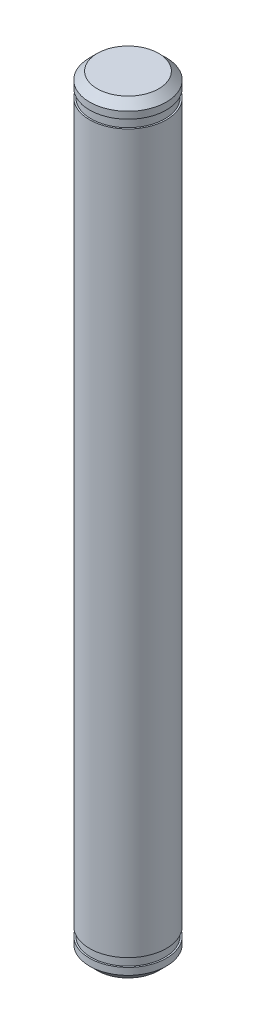
SolidWorks part; units mm, degrees
ref_plane "前视基准面" through (0, 0, 0) normal (0, 0, 1) x (1, 0, 0)
ref_plane "上视基准面" through (0, 0, 0) normal (0, 1, 0) x (1, 0, 0)
ref_plane "右视基准面" through (0, 0, 0) normal (1, 0, 0) x (0, 0, -1)
other "Configuration Table"
sketch "草图1" plane through (0, 0, 0) normal (0, 0, 1) x (1, 0, 0)
  line L0 (0, 17.9143) -> (0, -10.0949) construction
  line L1 (0, 40) -> (5, 40)
  line L2 (5, 40) -> (5, 30)
  line L4 (5, 30) -> (5, -49.5)
  line L6 (5, -49.5) -> (5, -59.5)
  line L7 (5, -59.5) -> (0, -59.5)
  line L8 (0, 0) -> (25.4592, 0) construction
  line L9 (0, 40) -> (0, -59.5)
  dimension "D1" = 5
  dimension "D3" = 79.5
  dimension "D4" = 10
  dimension "D5" = 10
revolve "旋转1" add sketch "草图1" angle 360 about L9
chamfer "倒角1" distance 1 angle 45 2 edges at (-5, -59.5, 0) (-5, 40, 0)
ref_plane "基准面1" through (0, -9.75, 0) normal (0, 1, 0) x (1, 0, 0)
sketch "草图2" plane through (0, 40, 0) normal (0, 1, 0) x (1, 0, 0)
  circle A0 centre (0, 0) radius 5 construction
  circle A1 centre (0, 0) radius 5
  circle A2 centre (0, 0) radius 4.8
  dimension "D1" = 9.6
extrude "切除-拉伸1" cut sketch "草图2" along normal blind 1.1 from offset 3 offset against normal yes
mirror "镜向1" about plane through (0, -9.75, 0) normal (0, 1, 0) of "切除-拉伸1"
